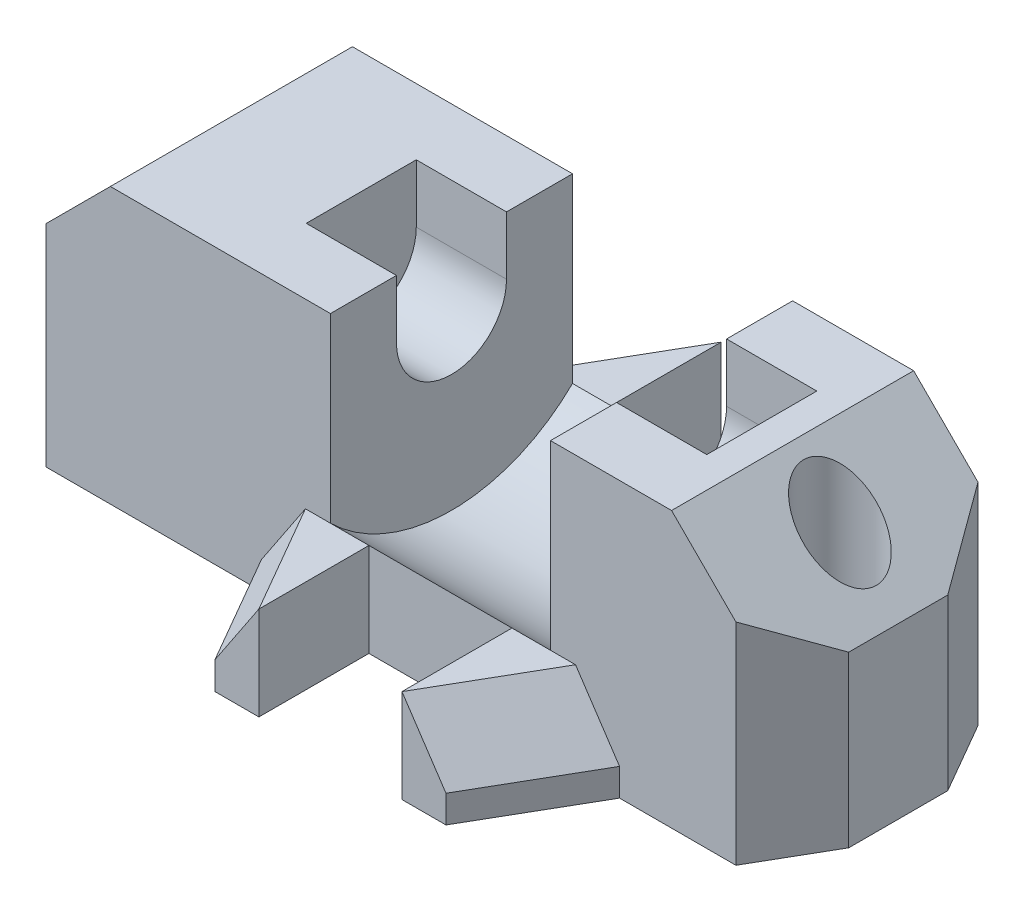
SolidWorks part; units mm, degrees
material "ABS"
ref_plane "Ebene vorne" through (0, 0, 0) normal (0, 0, 1) x (1, 0, 0)
ref_plane "Ebene oben" through (0, 0, 0) normal (0, 1, 0) x (1, 0, 0)
ref_plane "Ebene rechts" through (0, 0, 0) normal (1, 0, 0) x (0, 0, -1)
sketch "Skizze1" plane through (0, 0, 0) normal (0, 1, 0) x (1, 0, 0)
  line L0 (-0.7736, 5.5) -> (-30.5736, 5.5) construction
  line L1 (-16.4236, 12) -> (-10.4236, 12) construction
  line L2 (-16.4236, 12) -> (-16.4236, -1) construction
  line L3 (-16.4236, -1) -> (-10.4236, -1) construction
  line L4 (-10.4236, 12) -> (-10.4236, -1) construction
  line L5 (-13.4236, 12) -> (-13.4236, -1) construction
  line L6 (-3.4236, 8) -> (-23.4236, 8) construction
  line L7 (-3.4236, 8) -> (-3.4236, 3) construction
  line L8 (-3.4236, 3) -> (-23.4236, 3) construction
  line L9 (-23.4236, 8) -> (-23.4236, 3) construction
  line L10 (-23.4236, 10.25) -> (-27.9236, 10.25) construction
  line L11 (-23.4236, 10.25) -> (-23.4236, 0.75) construction
  line L12 (-23.4236, 0.75) -> (-27.9236, 0.75) construction
  line L13 (-27.9236, 10.25) -> (-27.9236, 0.75) construction
  line L14 (-17.4236, 13) -> (-16.4236, 13) construction
  line L15 (-17.4236, 13) -> (-17.4236, -2) construction
  line L16 (-17.4236, -2) -> (-16.4236, -2) construction
  line L17 (-16.4236, 13) -> (-16.4236, -2) construction
  line L18 (-9.4236, 13) -> (-10.4236, 13) construction
  line L19 (-9.4236, 13) -> (-9.4236, -2) construction
  line L20 (-9.4236, -2) -> (-10.4236, -2) construction
  line L21 (-10.4236, 13) -> (-10.4236, -2) construction
  line L23 (0, 11) -> (-31.3472, 11)
  line L24 (-31.3472, 0) -> (0, 0)
  line L25 (0, 11) -> (1.8764, 7.75)
  line L26 (1.8764, 7.75) -> (1.8764, 3.25)
  line L27 (1.8764, 3.25) -> (0, 0)
  line L28 (-15.6736, 11) -> (-15.6736, 0) construction
  line L29 (-33.2236, 3.25) -> (-31.3472, 0)
  line L30 (-33.2236, 7.75) -> (-33.2236, 3.25)
  line L31 (-31.3472, 11) -> (-33.2236, 7.75)
  line L32 (-9.4236, 10.25) -> (-8.4236, 10.25) construction
  line L33 (-9.4236, 10.25) -> (-9.4236, 0.75) construction
  line L34 (-9.4236, 0.75) -> (-8.4236, 0.75) construction
  line L35 (-8.4236, 10.25) -> (-8.4236, 0.75) construction
  line L36 (-17.4236, 10.25) -> (-18.4236, 10.25) construction
  line L37 (-17.4236, 10.25) -> (-17.4236, 0.75) construction
  line L38 (-17.4236, 0.75) -> (-18.4236, 0.75) construction
  line L39 (-18.4236, 10.25) -> (-18.4236, 0.75) construction
  circle A0 centre (-0.7736, 5.5) radius 1.65
  circle A1 centre (-30.5736, 5.5) radius 1.65
  circle A2 centre (6.5764, 11.5) radius 4.25 construction
  point P8 (-16.4236, 5.5)
  point P11 (-13.4236, 5.5)
  point P20 (-27.9236, 5.5)
  point P21 (-3.4236, 5.5)
  point P24 (2.3264, 11.5)
  point P25 (0.8764, 5.5)
  point P26 (-2.4236, 5.5)
  point P35 (-28.9236, 5.5)
  point P42 (1.8764, 5.5)
  point P49 (-32.2236, 5.5)
  point P56 (-8.4236, 5.5)
  dimension "D2" = 3.3
  dimension "D24" = 8.5
  dimension "D1" = 6
  dimension "D3" = 20
  dimension "D4" = 4.5
  dimension "D5" = 9.5
  dimension "D6" = 5
  dimension "D7" = 1
  dimension "D8" = 1.45
  dimension "D9" = 13
  dimension "D10" = 8
  dimension "D11" = 5
  dimension "D12" = 5
  dimension "D13" = 1
  dimension "D14" = 29.8
  dimension "D15" = 0.5
  dimension "D16" = 15
  dimension "D17" = 1
  dimension "D18" = 1
  dimension "D19" = 1
  dimension "D20" = 60
  dimension "D21" = 4.5
  dimension "D22" = 1
  dimension "D23" = 20
  dimension "D25" = 10.3
  dimension "D26" = 10
  dimension "D27" = 9.5
  dimension "D28" = 5.3
extrude "Aufsatz-Linear austragen1" add sketch "Skizze1" along normal blind 12.5
sketch "Skizze2" plane through (1.8764, 0, 0) normal (1, 0, 0) x (0, 0, -1)
  line L0 (7.75, 0) -> (11, 0) construction
  line L1 (3.25, 0) -> (7.75, 0) construction
  line L2 (0, 0) -> (3.25, 0) construction
  line L3 (0, 12.5) -> (0, 0) construction
  line L4 (11, 12.5) -> (11, 0) construction
  line L5 (7.75, 0) -> (11, 0) construction
  line L6 (3.25, 0) -> (7.75, 0) construction
  line L7 (0, 0) -> (3.25, 0) construction
  line L8 (0, 12.5) -> (0, 0) construction
  line L9 (11, 12.5) -> (11, 0) construction
  line L10 (5.5, 0) -> (5.5, 9.85) construction
  line L14 (3.25, 12.5) -> (7.75, 12.5) construction
  circle A0 centre (5.5, 9.85) radius 6.5 construction
  circle A1 centre (5.5, 9.85) radius 7.5 construction
  circle A2 centre (5.5, 9.85) radius 7.85
  circle A3 centre (5.5, 9.85) radius 2.5
  point P11 (5.5, 2)
  point P13 (5.5, 12.35)
  point P14 (5.5, 17.7)
  point P15 (5.5, 16.35)
  dimension "D1" = 13
  dimension "D2" = 15
  dimension "D3" = 15.7
  dimension "D5" = 5
  dimension "D4" = 2
  dimension "D6" = 3.85
  dimension "D7" = 0.15
extrude "Schnitt-Linear austragen1" cut sketch "Skizze2" against normal blind 10 from offset 10.3
sketch "Skizze3" plane through (1.8764, 0, 0) normal (1, 0, 0) x (0, 0, -1)
  line L0 (3, 12.5) -> (8, 12.5)
  line L1 (3, 9.85) -> (3, 12.5)
  line L2 (8, 9.85) -> (8, 12.5)
  line L3 (3.25, 12.5) -> (7.75, 12.5) construction
  circle A0 centre (5.5, 9.85) radius 2.5 construction
  circle A1 centre (5.5, 9.85) radius 2.5
  line M2 (7.75, 0) -> (7.75, 12.5)
  line M3 (7.75, 12.5) -> (3.25, 12.5)
  line M4 (3.25, 12.5) -> (3.25, 0)
extrude "Schnitt-Linear austragen2" cut sketch "Skizze3" against normal blind 20 from offset 5.3 contours A1 M2 M3 M4 | A1 L2 L0 M2 | A1 L0 L1 M4 | A1 M2 M4 | A1 M4 | A1 M2
sketch "Skizze4" plane through (-23.4236, 0, 0) normal (1, 0, 0) x (0, 0, -1)
  line L0 (10.25, 9.85) -> (10.25, 12.5)
  line L1 (0.75, 9.85) -> (0.75, 12.5)
  line L2 (0.75, 12.5) -> (10.25, 12.5)
  line L3 (8, 12.5) -> (3, 12.5) construction
  circle A0 centre (5.5, 9.85) radius 2.5 construction
  arc A1 (3, 9.85) -> (8, 9.85) centre (5.5, 9.85) ccw construction
  circle A2 centre (5.5, 9.85) radius 4.75
  line M1 (3, 12.5) -> (3, 9.85)
  arc M2 (3, 9.85) -> (8, 9.85) centre (5.5, 9.85) ccw
  line M3 (8, 9.85) -> (8, 12.5)
  line M4 (8, 12.5) -> (3, 12.5)
  dimension "D1" = 9.5
extrude "Schnitt-Linear austragen3" cut sketch "Skizze4" against normal blind 4.5 contours A2 L0 L2 | A2 L2 M3 M2 M1 | M4 M1 M2 M3 | A2 L2 L1
sketch "Skizze5" plane through (0, 0, 0) normal (0, 0, 1) x (1, 0, 0)
  line L0 (1.8764, 12.5) -> (-2.9236, 12.5)
  line L1 (-2.9236, 12.5) -> (1.8764, 7.7)
  line L2 (1.8764, 7.7) -> (1.8764, 12.5)
  line L3 (-33.2236, 12.5) -> (-28.4236, 12.5)
  line L4 (-28.4236, 12.5) -> (-33.2236, 7.7)
  line L5 (-33.2236, 7.7) -> (-33.2236, 12.5)
  line L6 (-8.4236, 12.5) -> (0, 12.5) construction
  line L7 (-33.2236, 12.5) -> (-33.2236, 0) construction
  line L8 (1.8764, 12.5) -> (1.8764, 0) construction
  line L9 (-3.4236, 12.5) -> (-2.4236, 12.5) construction
  point P12 (-3.4236, 12.5)
  point P13 (-2.4236, 12.5)
  point P18 (-2.9236, 12.5)
  dimension "D1" = 45
extrude "Schnitt-Linear austragen4" cut sketch "Skizze5" against normal up to surface (11 mm away)
sketch "Skizze6" plane through (0, 0, 0) normal (0, -1, 0) x (1, 0, 0)
  line L0 (-18.4236, -11) -> (-18.4236, 0) construction
  line L1 (-8.4236, 0) -> (-8.4236, -11) construction
  line L2 (-18.4236, -11) -> (-18.4236, 0) construction
  line L3 (-8.4236, 0) -> (-8.4236, -11) construction
  line L4 (-8.4236, -5.5) -> (-18.4236, -5.5) construction
  line L5 (-13.4236, 0) -> (-13.4236, -11) construction
  line L6 (-31.3472, 0) -> (0, 0) construction
  line L7 (0, -11) -> (-31.3472, -11) construction
  line L8 (-16.6736, 1) -> (-10.1736, 1) construction
  line L9 (-16.6736, 0) -> (-16.6736, 5)
  line L10 (-10.1736, 0) -> (-10.1736, 5)
  line L11 (-16.6736, -12) -> (-10.1736, -12) construction
  line L12 (-10.1736, 5) -> (-8.1736, 5)
  line L13 (-8.1736, 5) -> (-5.2869, 0)
  line L14 (-16.6736, 5) -> (-18.6736, 5)
  line L15 (-18.6736, 5) -> (-21.5604, 0)
  line L16 (-10.1736, 0) -> (-5.2869, 0)
  line L17 (-16.6736, 0) -> (-21.5604, 0)
  line L18 (-18.6736, -16) -> (-21.5604, -11)
  line L19 (-16.6736, -16) -> (-18.6736, -16)
  line L20 (-16.6736, -11) -> (-16.6736, -16)
  line L21 (-16.6736, -11) -> (-21.5604, -11)
  line L22 (-10.1736, -11) -> (-5.2869, -11)
  line L23 (-8.1736, -16) -> (-5.2869, -11)
  line L24 (-10.1736, -16) -> (-8.1736, -16)
  line L25 (-10.1736, -11) -> (-10.1736, -16)
  point P12 (-13.4236, -5.5)
  dimension "D1" = 6.5
  dimension "D2" = 13
  dimension "D3" = 4
  dimension "D4" = 2
  dimension "D5" = 60
  dimension "D6" = 60
extrude "Aufsatz-Linear austragen2" add sketch "Skizze6" against normal up to vertex (12.5 mm away)
chamfer "Fase1" distance 3 angle 30 4 edges at (-6.7302, 4.2489, -13.5) (-20.117, 4.2489, -13.5) (-6.7302, 4.2489, 2.5) (-20.117, 4.2489, 2.5)
sketch "Skizze7" plane through (-27.9236, 0, 0) normal (1, 0, 0) x (0, 0, -1)
  line L3 (10.25, 12.5) -> (0.75, 12.5)
  line L4 (0.75, 12.5) -> (0.75, 9.85)
  line L5 (10.25, 9.85) -> (10.25, 12.5)
  line L6 (10.25, 12.5) -> (0.75, 12.5)
  line L7 (0.75, 12.5) -> (0.75, 9.85)
  line L8 (10.25, 9.85) -> (10.25, 12.5)
  arc A1 (0.75, 9.85) -> (10.25, 9.85) centre (5.5, 9.85) ccw
  arc A2 (0.75, 9.85) -> (10.25, 9.85) centre (5.5, 9.85) ccw
  dimension "D1" = 0
extrude "Aufsatz-Linear austragen3" add sketch "Skizze7" along normal up to surface (4.5 mm away) up to face at (-23.4236, 10.2688, -5.5)
sketch "Skizze8" plane through (-23.4236, 0, 0) normal (1, 0, 0) x (0, 0, -1)
  line L3 (8, 12.5) -> (3, 12.5)
  line L4 (3, 12.5) -> (3, 9.85)
  line L5 (8, 9.85) -> (8, 12.5)
  line L6 (8, 12.5) -> (3, 12.5)
  line L7 (3, 12.5) -> (3, 9.85)
  line L8 (8, 9.85) -> (8, 12.5)
  arc A1 (3, 9.85) -> (8, 9.85) centre (5.5, 9.85) ccw
  arc A2 (3, 9.85) -> (8, 9.85) centre (5.5, 9.85) ccw
  dimension "D1" = 0
extrude "Aufsatz-Linear austragen4" add sketch "Skizze8" along normal blind 0.9
sketch "Skizze9" plane through (-3.4236, 0, 0) normal (-1, 0, 0) x (0, 0, 1)
  line L3 (-3, 9.85) -> (-3, 12.5)
  line L4 (-3, 12.5) -> (-8, 12.5)
  line L5 (-8, 12.5) -> (-8, 9.85)
  line L6 (-3, 9.85) -> (-3, 12.5)
  line L7 (-3, 12.5) -> (-8, 12.5)
  line L8 (-8, 12.5) -> (-8, 9.85)
  arc A1 (-8, 9.85) -> (-3, 9.85) centre (-5.5, 9.85) ccw
  arc A2 (-8, 9.85) -> (-3, 9.85) centre (-5.5, 9.85) ccw
  dimension "D1" = 0
extrude "Aufsatz-Linear austragen5" add sketch "Skizze9" along normal blind 0.9
